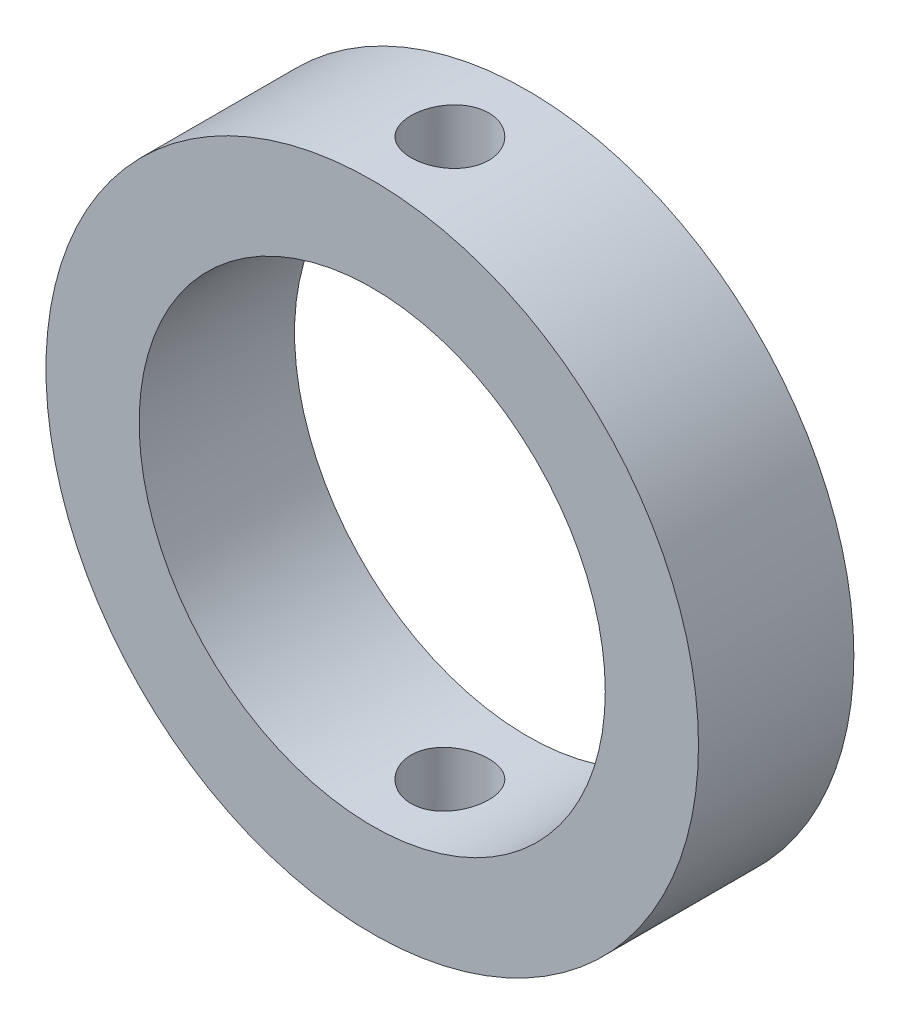
SolidWorks part; units mm, degrees
ref_plane "Front Plane" through (0, 0, 0) normal (0, 0, 1) x (1, 0, 0)
ref_plane "Top Plane" through (0, 0, 0) normal (0, 1, 0) x (1, 0, 0)
ref_plane "Right Plane" through (0, 0, 0) normal (1, 0, 0) x (0, 0, -1)
sketch "Sketch1" plane through (0, 0, 0) normal (0, 0, 1) x (1, 0, 0)
  circle A0 centre (0, 0) radius 30
  circle A1 centre (0, 0) radius 42
  dimension "D1" = 60
  dimension "D2" = 84
extrude "Boss-Extrude1" add sketch "Sketch1" along normal blind 20
sketch "Sketch2" plane through (0, 0, 0) normal (0, 1, 0) x (1, 0, 0)
  circle A0 centre (0, -10) radius 5
  dimension "D1" = 10
  dimension "D2" = 10
extrude "Cut-Extrude1" cut sketch "Sketch2" against normal through all both and the other way through all
